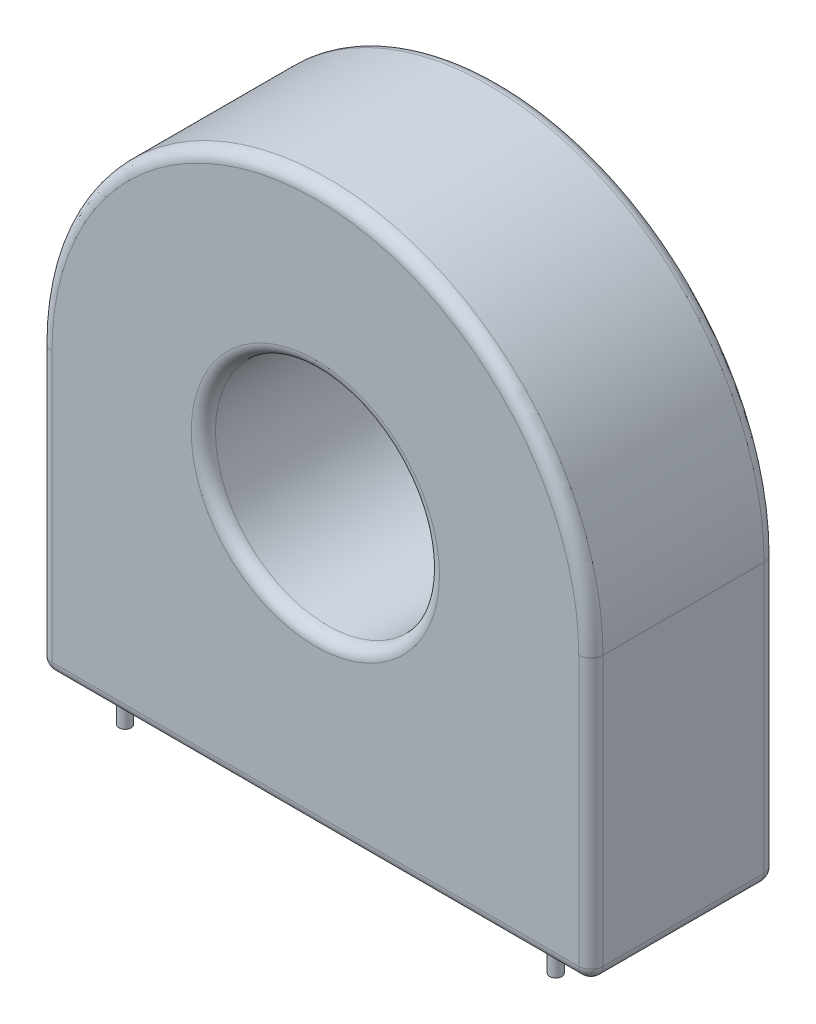
SolidWorks part; units mm, degrees
ref_plane "Front Plane" through (0, 0, 0) normal (0, 0, 1) x (1, 0, 0)
ref_plane "Top Plane" through (0, 0, 0) normal (0, 1, 0) x (1, 0, 0)
ref_plane "Right Plane" through (0, 0, 0) normal (1, 0, 0) x (0, 0, -1)
sketch "Sketch1" plane through (0, 0, 0) normal (0, 0, 1) x (1, 0, 0)
  line L0 (0, 56.047) -> (0, -94.9477) construction
  line L1 (0, 34.375) -> (50.579, 34.375) construction
  line L2 (-22.75, 11.625) -> (22.75, 11.625) construction
  line L3 (-22.75, 11.625) -> (-22.75, -11.625)
  line L4 (-22.75, -11.625) -> (22.75, -11.625)
  line L5 (22.75, 11.625) -> (22.75, -11.625)
  line L6 (-22.75, 11.625) -> (22.75, -11.625) construction
  line L7 (-22.75, -11.625) -> (22.75, 11.625) construction
  arc A0 (-22.75, 11.625) -> (22.75, 11.625) centre (0, 11.625) cw
  circle A1 centre (0, 11.625) radius 9.25
  point P2 (0, 0)
  dimension "D1" = 45.5
  dimension "D3" = 18.5
  dimension "D2" = 46
extrude "Boss-Extrude1" add sketch "Sketch1" along normal mid plane 15.3
sketch "Sketch2" plane through (0, -11.625, 0) normal (0, -1, 0) x (1, 0, 0)
  line L0 (0, 13.15) -> (0, 0) construction
  line L1 (0, 0) -> (25.5661, 0) construction
  line L2 (17.78, 5.58) -> (28.4302, 5.58) construction
  line L3 (-22.75, 7.65) -> (22.75, 7.65) construction
  circle A0 centre (17.78, 5.58) radius 0.5
  circle A1 centre (0, -4.58) radius 0.5
  circle A2 centre (-17.78, 5.58) radius 0.5
  dimension "D1" = 10.16
  dimension "D4" = 1
  dimension "D2" = 17.78
  dimension "D3" = 2.07
extrude "Boss-Extrude2" add sketch "Sketch2" along normal mid plane 5
fillet "Fillet1" radius 1 11 edges at (-22.75, 0, -7.65) (0, 34.375, -7.65) (22.75, 0, 7.65) (-22.75, 0, 7.65) (-22.75, -11.625, 0) (22.75, -11.625, 0) (0, -11.625, -7.65) (0, -11.625, 7.65) (22.75, 0, -7.65) (0, 34.375, 7.65) (9.25, 11.625, 7.65)
sketch "Sketch3" plane through (0, 0, -7.65) normal (0, 0, 1) x (1, 0, 0)
  line L0 (-19.836, -3.856) -> (19.836, -3.856) construction
  line L1 (-19.836, -9.106) -> (19.836, -9.106) construction
  text T0 "THAI LIN " font "Xolonium" height 4
  text T1 "TL76-5-100" font "Xolonium" height 4
  point P2 (0, -3.856)
  dimension "D1" = 5.25
extrude "Cut-Extrude1" cut sketch "Sketch3" along normal blind 0.01
sketch "Sketch4" plane through (0, -11.625, 0) normal (0, -1, 0) x (1, 0, 0)
  line L0 (-20.7266, 3.7883) -> (20.0523, 3.7883) construction
  line L1 (-5.0577, -0.3768) -> (5.4385, -0.3768) construction
  text T0 " #1                             #2" font "Xolonium" height 3
  text T1 "#3" font "Xolonium" height 3
  point P10 (0.1904, -0.3768)
extrude "Cut-Extrude2" cut sketch "Sketch4" against normal blind 0.01
